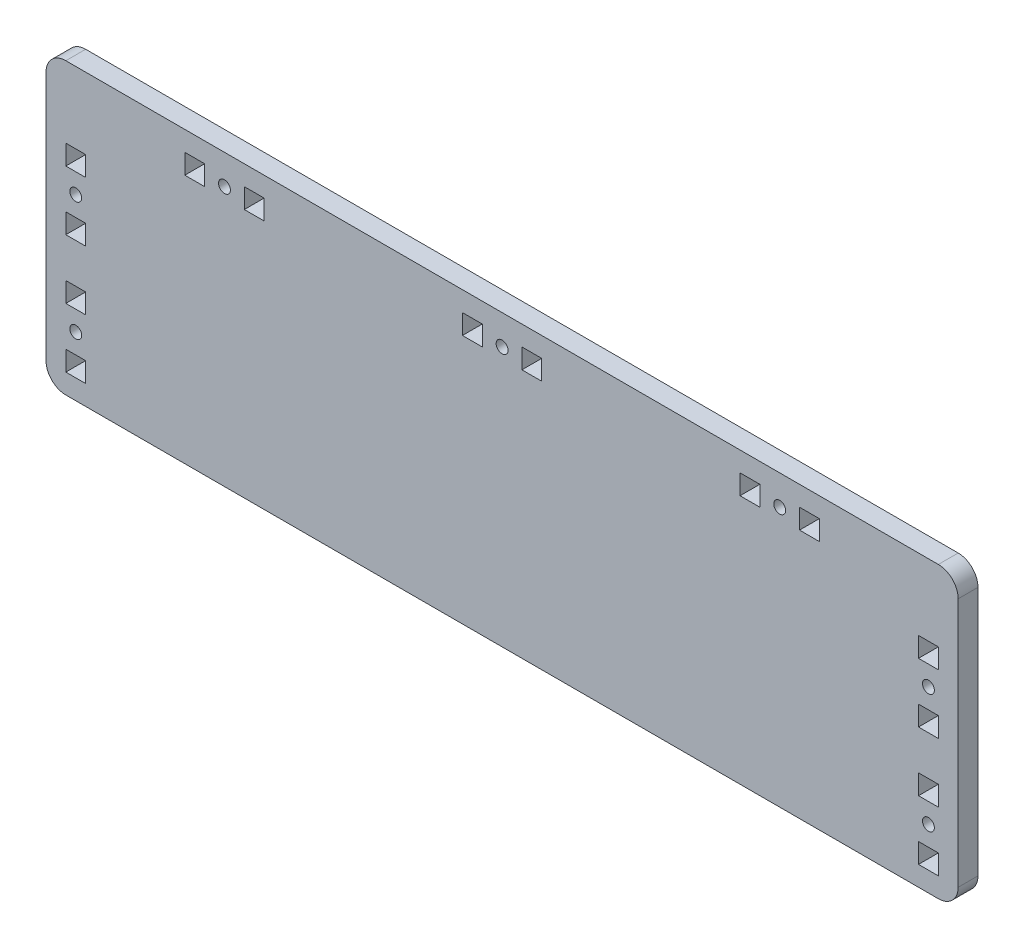
SolidWorks part; units mm, degrees
ref_plane "Plan de face" through (0, 0, 0) normal (0, 0, 1) x (1, 0, 0)
ref_plane "Plan de dessus" through (0, 0, 0) normal (0, 1, 0) x (1, 0, 0)
ref_plane "Plan de droite" through (0, 0, 0) normal (1, 0, 0) x (0, 0, -1)
sketch "Esquisse1" plane through (0, 0, 0) normal (0, 0, 1) x (1, 0, 0)
  line L0 (0, 0) -> (0, 73) construction
  line L1 (-115, 73) -> (115, 73)
  line L2 (-115, 73) -> (-115, 0)
  line L3 (-115, 0) -> (115, 0)
  line L4 (115, 73) -> (115, 0)
  point P6 (0, 0)
  point P8 (80.3391, 37.9783)
  point P10 (85.3557, -8.404)
  point P11 (0, 0)
  point P12 (5, 71.3485)
  point P13 (91.0035, 74.3314)
  line B0 (105, 40) -> (105, 35)
  line B1 (105, 40) -> (110, 40)
  line B2 (110, 40) -> (110, 35)
  line B3 (105, 35) -> (110, 35)
  line B4 (105, 50) -> (105, 55)
  line B5 (105, 50) -> (110, 50)
  line B6 (110, 50) -> (110, 55)
  line B7 (105, 55) -> (110, 55)
  line B8 (107.5, 45) -> (101.2198, 45) construction
  circle B9 centre (107.5, 45) radius 1.5
  line B10 (105, 10) -> (105, 5)
  line B11 (105, 10) -> (110, 10)
  line B12 (110, 10) -> (110, 5)
  line B13 (105, 5) -> (110, 5)
  line B14 (105, 20) -> (105, 25)
  line B15 (105, 20) -> (110, 20)
  line B16 (110, 20) -> (110, 25)
  line B17 (105, 25) -> (110, 25)
  line B18 (107.5, 15) -> (101.2198, 15) construction
  circle B19 centre (107.5, 15) radius 1.5
  line B20 (-105, 10) -> (-105, 5)
  line B21 (-105, 10) -> (-110, 10)
  line B22 (-110, 10) -> (-110, 5)
  line B23 (-105, 5) -> (-110, 5)
  line B24 (-105, 20) -> (-105, 25)
  line B25 (-105, 20) -> (-110, 20)
  line B26 (-110, 20) -> (-110, 25)
  line B27 (-105, 25) -> (-110, 25)
  circle B28 centre (-107.5, 15) radius 1.5
  line B29 (-105, 40) -> (-105, 35)
  line B30 (-105, 40) -> (-110, 40)
  line B31 (-110, 40) -> (-110, 35)
  line B32 (-105, 35) -> (-110, 35)
  line B33 (-105, 50) -> (-105, 55)
  line B34 (-105, 50) -> (-110, 50)
  line B35 (-110, 50) -> (-110, 55)
  line B36 (-105, 55) -> (-110, 55)
  circle B37 centre (-107.5, 45) radius 1.5
  line B38 (5, 68) -> (10, 68)
  line B39 (5, 68) -> (5, 63)
  line B40 (5, 63) -> (10, 63)
  line B41 (10, 68) -> (10, 63)
  line B42 (-5, 68) -> (-10, 68)
  line B43 (-5, 68) -> (-5, 63)
  line B44 (-5, 63) -> (-10, 63)
  line B45 (-10, 68) -> (-10, 63)
  line B46 (0, 65.5) -> (0, 71.7802) construction
  circle B47 centre (0, 65.5) radius 1.5
  line B48 (75, 68) -> (80, 68)
  line B49 (75, 68) -> (75, 63)
  line B50 (75, 63) -> (80, 63)
  line B51 (80, 68) -> (80, 63)
  line B52 (65, 68) -> (60, 68)
  line B53 (65, 68) -> (65, 63)
  line B54 (65, 63) -> (60, 63)
  line B55 (60, 68) -> (60, 63)
  line B56 (70, 65.5) -> (70, 71.7802) construction
  circle B57 centre (70, 65.5) radius 1.5
  line B58 (-75, 68) -> (-80, 68)
  line B59 (-75, 68) -> (-75, 63)
  line B60 (-75, 63) -> (-80, 63)
  line B61 (-80, 68) -> (-80, 63)
  line B62 (-65, 68) -> (-60, 68)
  line B63 (-65, 68) -> (-65, 63)
  line B64 (-65, 63) -> (-60, 63)
  line B65 (-60, 68) -> (-60, 63)
  circle B66 centre (-70, 65.5) radius 1.5
  dimension "D1" = 5
  dimension "D2" = 30
  dimension "D3" = 8
  dimension "D4" = 5
  dimension "D5" = 210
  dimension "D6" = 5
  dimension "D7" = 70
sketch_block_instance "Trou M3 plots 5mm-52"
sketch_block "Trou M3 plots 5mm" parameters "D2"=3, "D1"=5, "D3"=5, "D4"=8
sketch_block_instance "Trou M3 plots 5mm-53"
sketch_block_instance "Trou M3 plots 5mm-55"
sketch_block_instance "Trou M3 plots 5mm-56"
sketch_block_instance "Trou M3 plots 5mm-57"
sketch_block_instance "Trou M3 plots 5mm-58"
sketch_block_instance "Trou M3 plots 5mm-59"
extrude "Boss.-Extru.1" add sketch "Esquisse1" along normal blind 5
fillet "Congé1" radius 5 4 edges at (115, 0, 2.5) (115, 73, 2.5) (-115, 0, 2.5) (-115, 73, 2.5)
